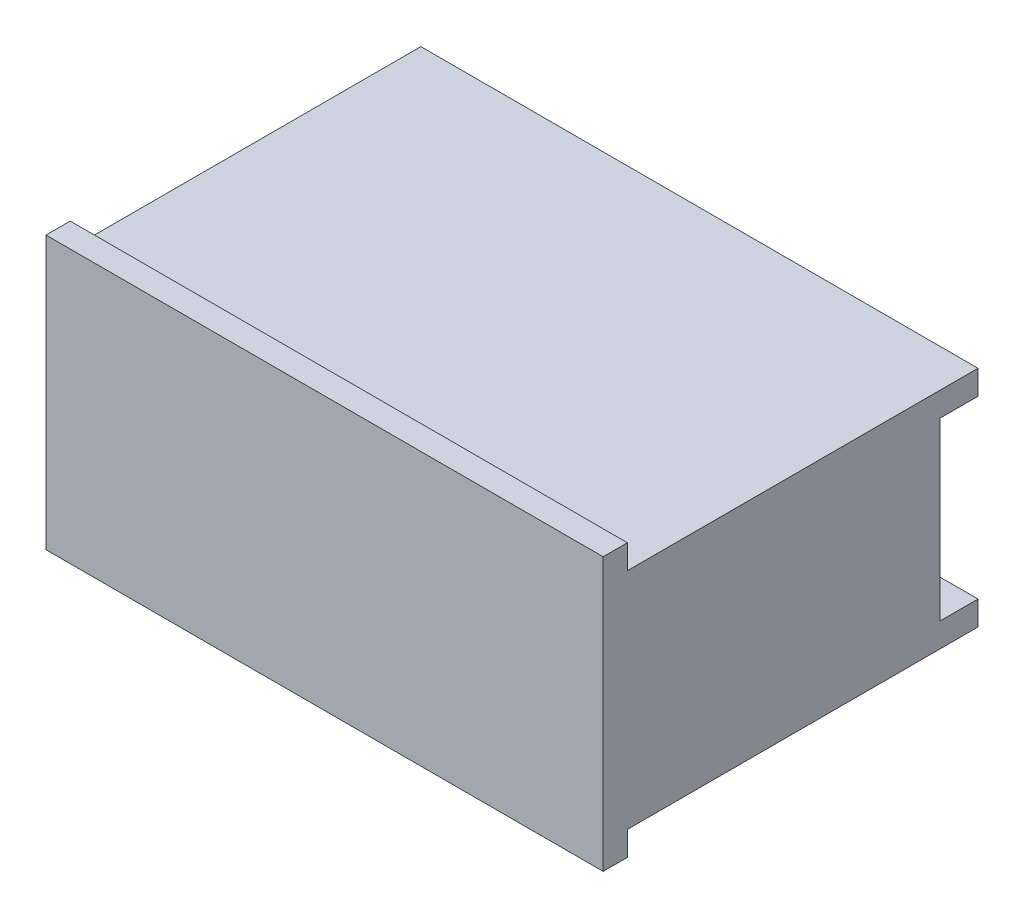
SolidWorks part; units mm, degrees
ref_plane "Ön Düzlem" through (0, 0, 0) normal (0, 0, 1) x (1, 0, 0)
ref_plane "Üst Düzlem" through (0, 0, 0) normal (0, 1, 0) x (1, 0, 0)
ref_plane "Sağ Düzlem" through (0, 0, 0) normal (1, 0, 0) x (0, 0, -1)
sketch "Çizim1" plane through (0, 0, 0) normal (0, 0, 1) x (1, 0, 0)
  line L1 (-23, 9.25) -> (23, 9.25)
  line L2 (-23, 9.25) -> (-23, -9.25)
  line L3 (-23, -9.25) -> (23, -9.25)
  line L4 (23, 9.25) -> (23, -9.25)
  line L5 (-23, 9.25) -> (23, -9.25) construction
  line L6 (-23, -9.25) -> (23, 9.25) construction
  point P0 (0, 0)
  dimension "D1" = 18.5
  dimension "D2" = 46
extrude "Yükseklik-Ekstrüzyon1" add sketch "Çizim1" against normal blind 30.95
sketch "Çizim2" plane through (0, 0, -30.95) normal (0, 0, -1) x (-1, 0, 0)
  line L1 (-23, 7.25) -> (23, 7.25)
  line L2 (-23, 7.25) -> (-23, -7.25)
  line L3 (-23, -7.25) -> (23, -7.25)
  line L4 (23, 7.25) -> (23, -7.25)
  line L5 (-23, 7.25) -> (23, -7.25) construction
  line L6 (-23, -7.25) -> (23, 7.25) construction
  point P0 (0, 0)
  dimension "D1" = 14.5
  dimension "D2" = 46
extrude "Kes-Ekstrüzyon1" cut sketch "Çizim2" against normal blind 3.15
sketch "Çizim3" plane through (0, -9.25, 0) normal (0, -1, 0) x (1, 0, 0)
  line L0 (-23, -30.95) -> (-23, 0) construction
  line L1 (-23, 0) -> (23, 0)
  line L2 (-23, 0) -> (-23, -2)
  line L3 (-23, -2) -> (23, -2)
  line L4 (23, 0) -> (23, -2)
  line L5 (-23, 0) -> (23, -2) construction
  line L6 (-23, -2) -> (23, 0) construction
  line L7 (12.375, 0) -> (-12.375, 0) construction
  point P0 (0, -1)
  dimension "D1" = 46
  dimension "D2" = 0
  dimension "D3" = 0
  dimension "D4" = 2
extrude "Yükseklik-Ekstrüzyon2" add sketch "Çizim3" along normal blind 2
sketch "Çizim4" plane through (0, 9.25, 0) normal (0, 1, 0) x (1, 0, 0)
  line L0 (23, 30.95) -> (23, 0) construction
  line L1 (-23, 2) -> (23, 2)
  line L2 (-23, 2) -> (-23, 0)
  line L3 (-23, 0) -> (23, 0)
  line L4 (23, 2) -> (23, 0)
  line L5 (-23, 2) -> (23, 0) construction
  line L6 (-23, 0) -> (23, 2) construction
  line L7 (-12.375, 0) -> (12.375, 0) construction
  point P0 (0, 1)
  dimension "D1" = 0
  dimension "D2" = 0
  dimension "D3" = 2
  dimension "D4" = 46
extrude "Yükseklik-Ekstrüzyon3" add sketch "Çizim4" along normal blind 2
